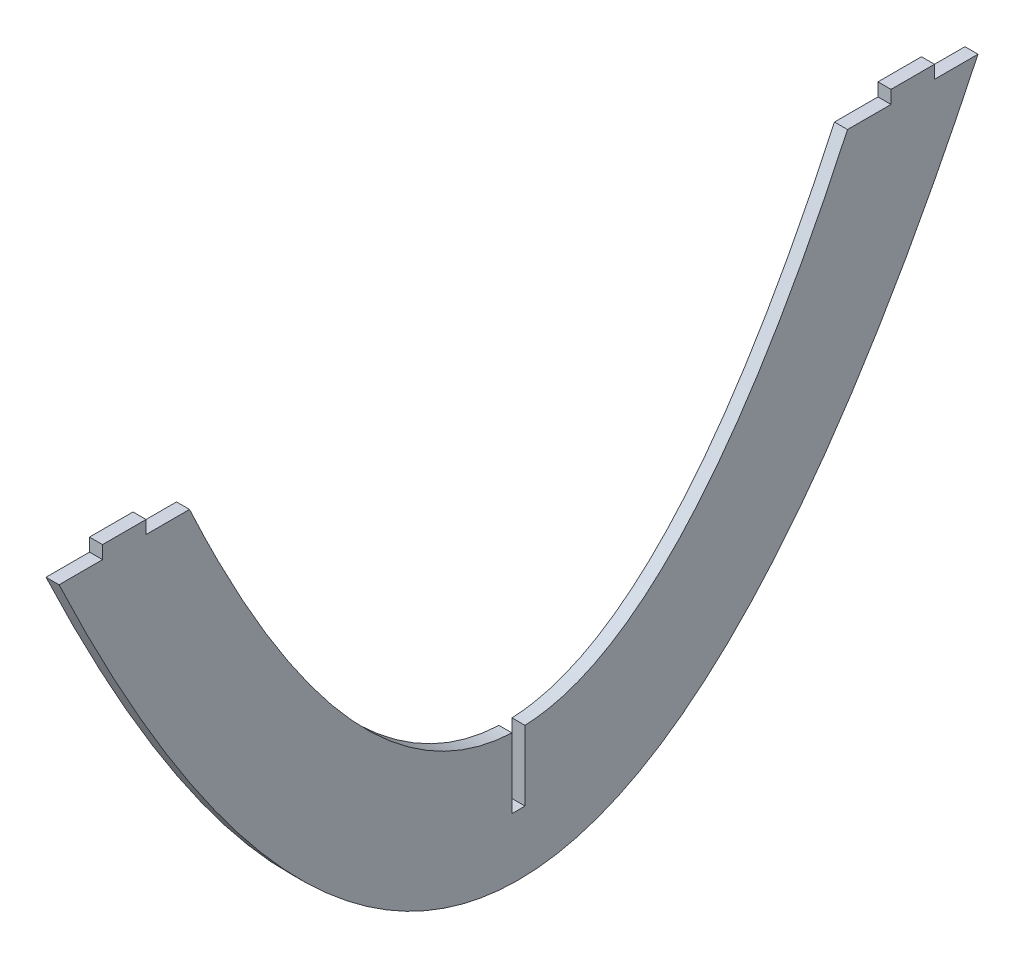
SolidWorks part; units mm, degrees
ref_plane "前视基准面" through (0, 0, 0) normal (0, 0, 1) x (1, 0, 0)
ref_plane "上视基准面" through (0, 0, 0) normal (0, 1, 0) x (1, 0, 0)
ref_plane "右视基准面" through (0, 0, 0) normal (1, 0, 0) x (0, 0, -1)
sketch "草图1" plane through (0, 0, 0) normal (1, 0, 0) x (0, 0, -1)
  line L0 (-105.6416, 150.0009) -> (-75.642, 150.0009)
  line L1 (75.642, 150.0009) -> (105.6416, 150.0009)
  spline S0 degree 2 poles (-118.7643, 179.4489) (0, -102.65) (118.7643, 179.4489) knots 0 0 0 1 1 1 construction
  spline S1 degree 2 poles (-105.6416, 150.0009) (0, -73.202) (105.6416, 150.0009) knots 0.055247 0.055247 0.055247 0.944753 0.944753 0.944753
  spline S2 degree 2 poles (-117.6312, 265.7401) (0, -128.9412) (117.6312, 265.7401) knots 0 0 0 1 1 1 construction
  spline S3 degree 2 poles (-75.642, 150.0009) (0, -13.202) (75.642, 150.0009) knots 0.178478 0.178478 0.178478 0.821522 0.821522 0.821522
extrude "凸台-拉伸1" add sketch "草图1" along normal blind 3
sketch "草图2" plane through (0, 150.0009, 0) normal (0, 1, 0) x (1, 0, 0)
  line L0 (0, -105.6416) -> (3, -75.642)
  line L1 (0, 75.642) -> (3, 105.6416)
  line L2 (0, 105.6416) -> (0, 75.642) construction
  line L3 (3, 85.6418) -> (0, 85.6418)
  line L4 (3, 85.6418) -> (3, 95.6418)
  line L5 (3, 95.6418) -> (0, 95.6418)
  line L6 (0, 85.6418) -> (0, 95.6418)
  line L7 (3, 85.6418) -> (0, 95.6418) construction
  line L8 (3, 95.6418) -> (0, 85.6418) construction
  line L9 (0, -75.642) -> (0, -105.6416) construction
  line L10 (3, -95.6418) -> (0, -95.6418)
  line L11 (3, -95.6418) -> (3, -85.6418)
  line L12 (3, -85.6418) -> (0, -85.6418)
  line L13 (0, -95.6418) -> (0, -85.6418)
  line L14 (3, -95.6418) -> (0, -85.6418) construction
  line L15 (3, -85.6418) -> (0, -95.6418) construction
  point P8 (1.5, 90.6418)
  point P15 (1.5, -90.6418)
  line M2 (0, -75.642) -> (0, -105.6416)
  line M4 (3, -105.6416) -> (3, -75.642)
extrude "凸台-拉伸2" add sketch "草图2" along normal blind 3 contours L6 L3 L1 L5 | L4 L5 L1 L3 | L0 L12 L10 M2 | L12 L0 L10 M4
sketch "草图3" plane through (0, 0, 0) normal (-1, 0, 0) x (0, 0, 1)
  line L0 (-1.5, 52.3673) -> (-1.5, 39.8523) construction
  line L1 (-1.5, 52.3673) -> (-1.5, 39.8523)
  line L2 (1.5, 52.3673) -> (1.5, 39.8523) construction
  line L3 (1.5, 52.3673) -> (1.5, 39.8523)
  line L5 (-1.5, 52.3673) -> (1.5, 52.3673)
  line L6 (-1.5, 52.3673) -> (-1.5, 74.3364)
  line L7 (-1.5, 74.3364) -> (1.5, 74.3364)
  line L8 (1.5, 52.3673) -> (1.5, 74.3364)
  spline M1 degree 2 poles (75.642, 150.0009) (0, -13.202) (-75.642, 150.0009) knots 0.178478 0.178478 0.178478 0.821522 0.821522 0.821522
extrude "切除-拉伸1" cut sketch "草图3" against normal through all contours L5 L8 L6 M1
